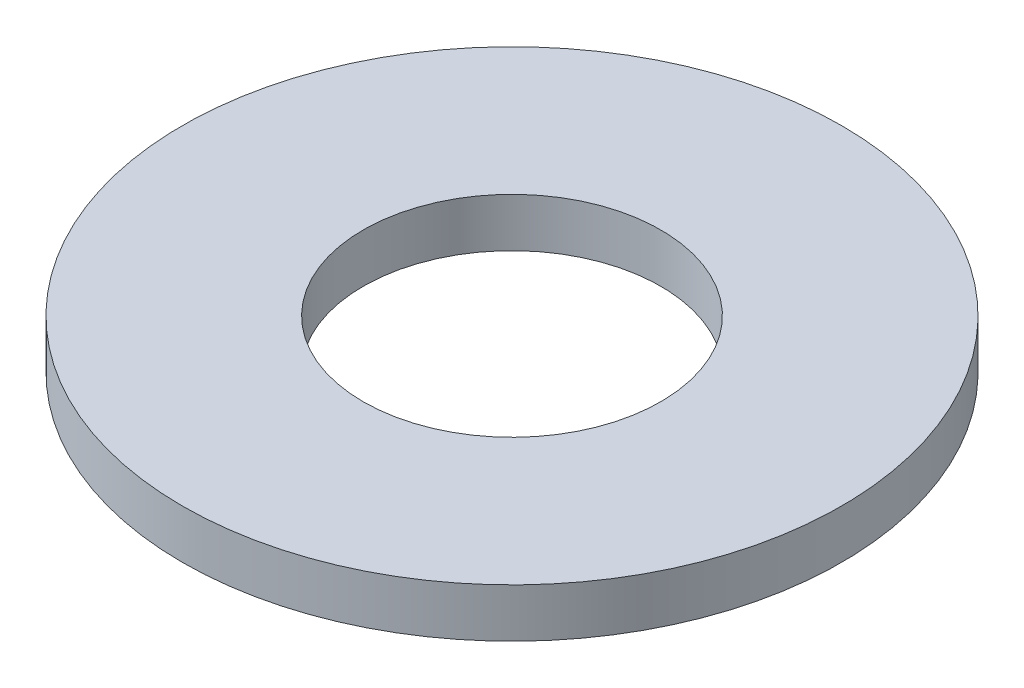
SolidWorks part; units mm, degrees
ref_plane "Front Plane" through (0, 0, 0) normal (0, 0, 1) x (1, 0, 0)
ref_plane "Top Plane" through (0, 0, 0) normal (0, 1, 0) x (1, 0, 0)
ref_plane "Right Plane" through (0, 0, 0) normal (1, 0, 0) x (0, 0, -1)
sketch "Sketch1" plane through (0, 0, 0) normal (0, 1, 0) x (1, 0, 0)
  circle A0 centre (0, 0) radius 3.375
  circle A1 centre (0, 0) radius 1.524
  dimension "D1" = 6.75
  dimension "D2" = 3.048
extrude "Boss-Extrude1" add sketch "Sketch1" along normal blind 0.5
